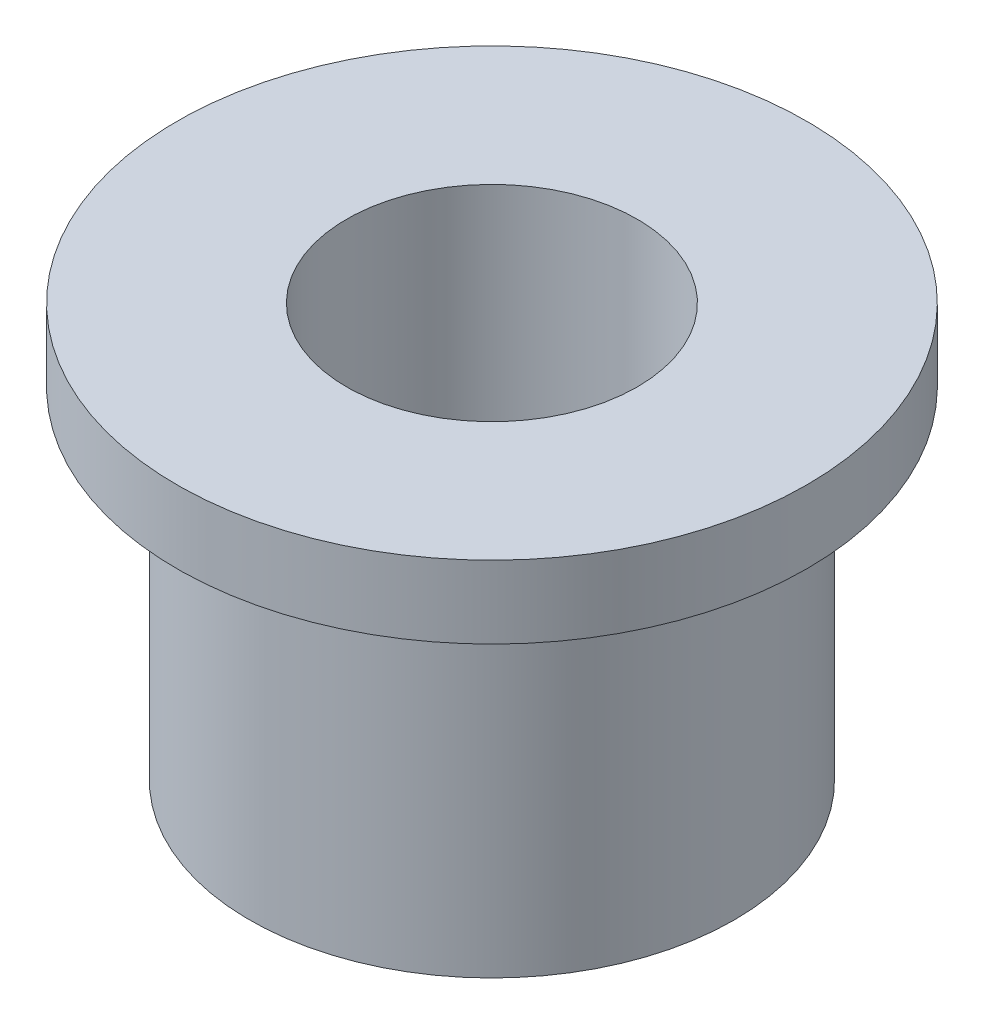
SolidWorks part; units mm, degrees
ref_plane "前视基准面" through (0, 0, 0) normal (0, 0, 1) x (1, 0, 0)
ref_plane "上视基准面" through (0, 0, 0) normal (0, 1, 0) x (1, 0, 0)
ref_plane "右视基准面" through (0, 0, 0) normal (1, 0, 0) x (0, 0, -1)
sketch "草图1" plane through (0, 0, 0) normal (0, 0, 1) x (1, 0, 0)
  line L0 (0, -171.5579) -> (0, 8406.3357) construction
  line L1 (5, 7.0287) -> (5, 0)
  line L2 (-6.5, 8.5287) -> (0, 8.5287)
  line L3 (-6.5, 8.5287) -> (-6.5, 7.0287)
  line L4 (-6.5, 7.0287) -> (0, 7.0287)
  line L5 (6.5, 8.5287) -> (6.5, 7.0287)
  line L6 (-6.5, 8.5287) -> (0, 7.7787) construction
  line L7 (-6.5, 7.0287) -> (0, 7.7787) construction
  line L8 (5, 0) -> (3, 0)
  line L9 (0, 0) -> (0, 7.0287)
  line L10 (0, 7.0287) -> (0, 8.5287)
  line L11 (3, 8.5287) -> (3, 0)
  line L12 (5, 7.0287) -> (6.5, 7.0287)
  line L13 (3, 7.4325) -> (6.5, 7.0287) construction
  line L14 (3, 8.1248) -> (6.5, 8.5287) construction
  line L15 (3, 8.5287) -> (6.5, 8.5287)
  point P1 (0, 7.7787)
  dimension "D1" = 13
  dimension "D2" = 1.5
  dimension "D3" = 3
  dimension "D4" = 5
revolve "旋转1" add sketch "草图1" angle 360 about L0
